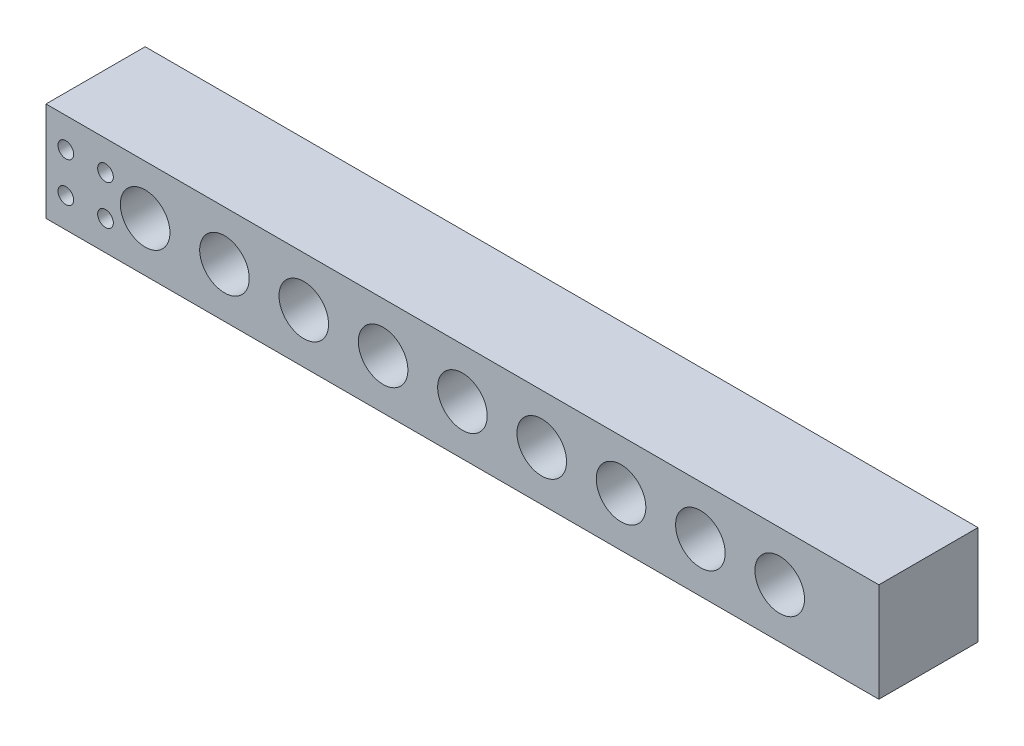
SolidWorks part; units mm, degrees
material "6061-T6 (SS)"
ref_plane "Front Plane" through (0, 0, 0) normal (0, 0, 1) x (1, 0, 0)
ref_plane "Top Plane" through (0, 0, 0) normal (0, 1, 0) x (1, 0, 0)
ref_plane "Right Plane" through (0, 0, 0) normal (1, 0, 0) x (0, 0, -1)
sketch "Sketch1" plane through (0, 0, 0) normal (0, 0, 1) x (1, 0, 0)
  line L1 (0, 0) -> (-266.7, 0)
  line L2 (0, 0) -> (0, -31.75)
  line L3 (0, -31.75) -> (-266.7, -31.75)
  line L4 (-266.7, 0) -> (-266.7, -31.75)
  dimension "D1" = 266.7
  dimension "D2" = 31.75
extrude "Boss-Extrude1" add sketch "Sketch1" along normal blind 31.75
sketch "Sketch2" plane through (0, 0, 31.75) normal (0, 0, 1) x (1, 0, 0)
  line L0 (-266.7, -31.75) -> (0, -31.75) construction
  line L1 (-266.7, 0) -> (-266.7, -31.75) construction
  circle A0 centre (-234.95, -15.875) radius 7.9375
  dimension "D1" = 15.875
  dimension "D3" = 15.875
  dimension "D2" = 31.75
extrude "Cut-Extrude1" cut sketch "Sketch2" against normal blind 31.75
pattern_linear "LPattern1" count 9 spacing 25.4 along (1, 0, 0) of "Cut-Extrude1"
sketch "Sketch3" plane through (0, 0, 31.75) normal (0, 0, 1) x (1, 0, 0)
  line L0 (-266.7, -31.75) -> (0, -31.75) construction
  line L1 (-266.7, 0) -> (-266.7, -31.75) construction
  circle A0 centre (-260.35, -9.525) radius 2.5082
  circle A1 centre (-247.65, -9.525) radius 2.5082
  circle A2 centre (-260.35, -22.225) radius 2.5082
  circle A3 centre (-247.65, -22.225) radius 2.5082
  point P8 (-254, -15.875)
  dimension "D1" = 5.0165
  dimension "D2" = 15.875
  dimension "D3" = 12.7
  dimension "D4" = 6.35
  dimension "D5" = 6.35
  dimension "D6" = 6.35
  dimension "D7" = 6.35
  dimension "D8" = 6.35
  dimension "D9" = 6.35
  dimension "D10" = 6.35
  dimension "D11" = 6.35
extrude "Cut-Extrude2" cut sketch "Sketch3" against normal blind 31.75
